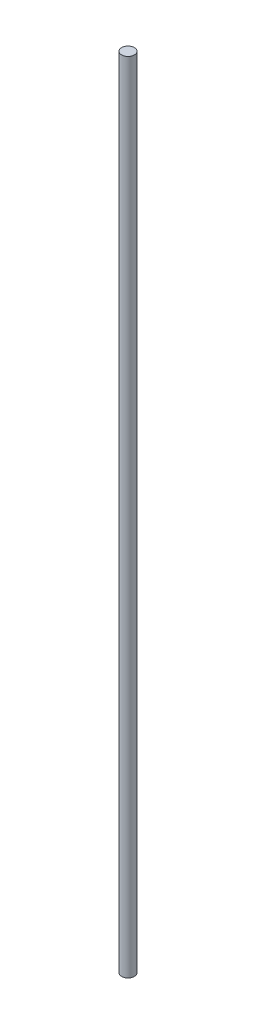
SolidWorks part; units mm, degrees
ref_plane "Front Plane" through (0, 0, 0) normal (0, 0, 1) x (1, 0, 0)
ref_plane "Top Plane" through (0, 0, 0) normal (0, 1, 0) x (1, 0, 0)
ref_plane "Right Plane" through (0, 0, 0) normal (1, 0, 0) x (0, 0, -1)
sketch "Sketch1" plane through (0, 0, 0) normal (0, 1, 0) x (1, 0, 0)
  circle A0 centre (0, 0) radius 6
  dimension "D1" = 12
extrude "Boss-Extrude1" add sketch "Sketch1" along normal blind 750
